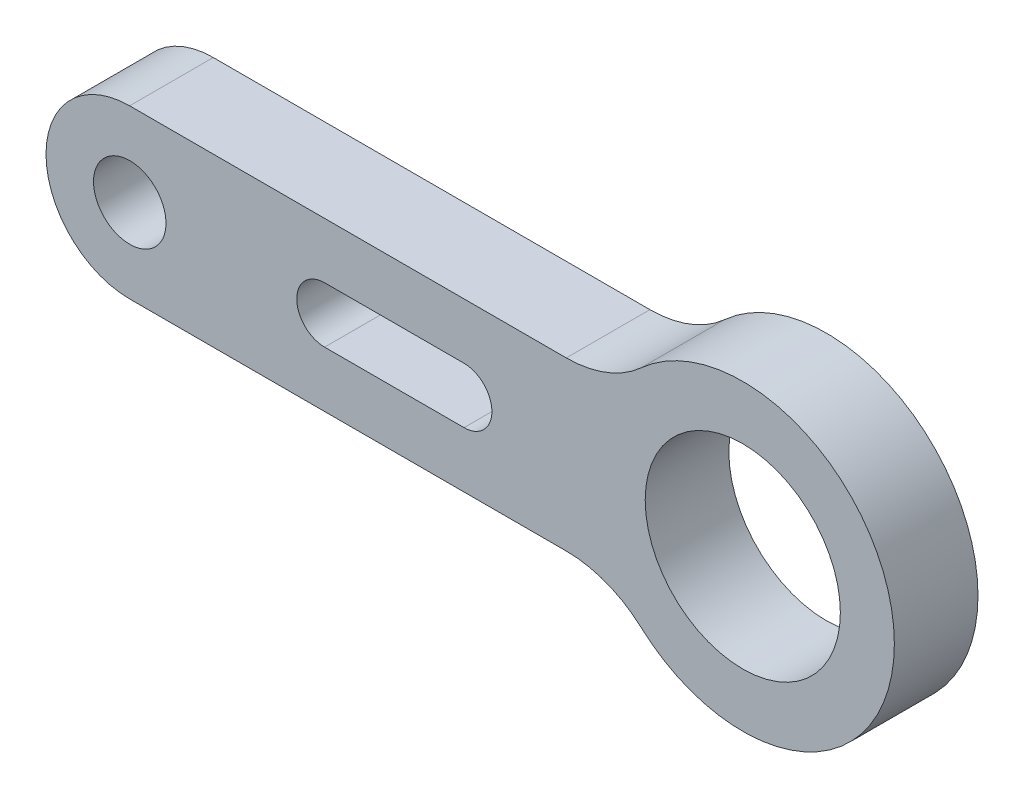
SolidWorks part; units mm, degrees
ref_plane "前视基准面" through (0, 0, 0) normal (0, 0, 1) x (1, 0, 0)
ref_plane "上视基准面" through (0, 0, 0) normal (0, 1, 0) x (1, 0, 0)
ref_plane "右视基准面" through (0, 0, 0) normal (1, 0, 0) x (0, 0, -1)
ref_plane "基准面1" through (0, 0, 3) normal (0, 0, 1) x (1, 0, 0)
sketch "草图1" plane through (0, 0, 3) normal (0, 0, 1) x (1, 0, 0)
  line L0 (17.5428, 6.9071) -> (1.8798, 6.9071)
  line L1 (1.8798, 0.9071) -> (17.5441, 0.9071)
  line L2 (8.874, 4.9074) -> (13.874, 4.9074)
  line L3 (13.874, 2.9074) -> (8.874, 2.9074)
  circle A0 centre (23.873, 3.9077) radius 3.5
  arc A1 (20.2266, -0.1257) -> (20.2258, 7.9404) centre (23.873, 3.9077) ccw
  arc A2 (20.2258, 7.9404) -> (17.5428, 6.9071) centre (17.5428, 10.9071) cw
  arc A3 (1.8798, 6.9071) -> (1.8798, 0.9071) centre (1.8798, 3.9071) ccw
  arc A4 (17.5441, 0.9071) -> (20.2266, -0.1257) centre (17.5441, -3.0929) cw
  arc A5 (8.874, 2.9074) -> (8.874, 4.9074) centre (8.874, 3.9074) cw
  arc A6 (13.874, 4.9074) -> (13.874, 2.9074) centre (13.874, 3.9074) cw
  circle A7 centre (1.884, 3.9071) radius 1.3
extrude "凸台-拉伸1" add sketch "草图1" against normal blind 3
